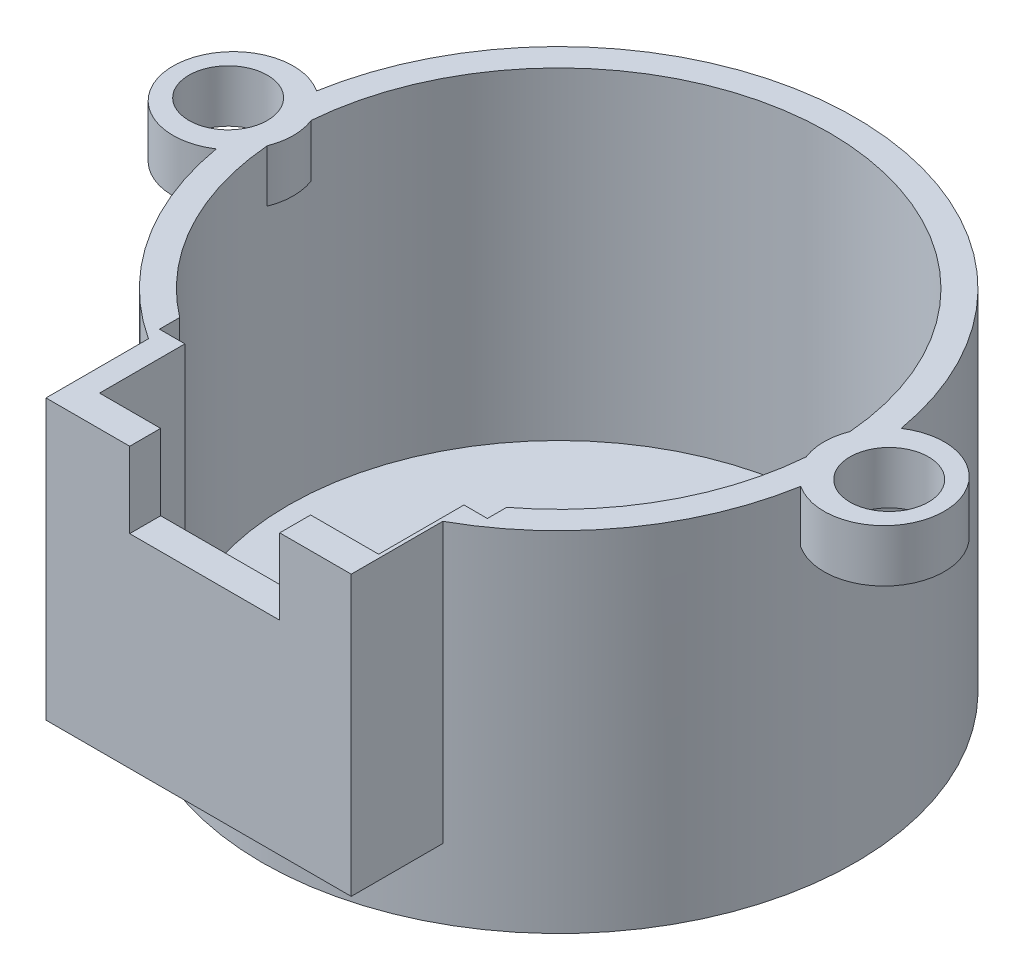
SolidWorks part; units mm, degrees
ref_plane "Front Plane" through (0, 0, 0) normal (0, 0, 1) x (1, 0, 0)
ref_plane "Top Plane" through (0, 0, 0) normal (0, 1, 0) x (1, 0, 0)
ref_plane "Right Plane" through (0, 0, 0) normal (1, 0, 0) x (0, 0, -1)
sketch "Sketch1" plane through (0, 0, 0) normal (0, 1, 0) x (1, 0, 0)
  circle A0 centre (0, 0) radius 17
  dimension "D1" = 34
extrude "Boss-Extrude1" add sketch "Sketch1" along normal blind 20
shell "Shell1" thickness 1.5
sketch "Sketch2" plane through (0, 20, 0) normal (0, 1, 0) x (1, 0, 0)
  line L0 (-15.5, 0) -> (37.717, 0) construction
  line L1 (0, 0) -> (0, -36.0151) construction
  circle A0 centre (0, 0) radius 15.5 construction
  circle A3 centre (18.6594, 0) radius 3.45
  circle A4 centre (-18.6594, 0) radius 3.45
extrude "Boss-Extrude3" add sketch "Sketch2" against normal blind 3
sketch "Sketch4" plane through (0, 20, 0) normal (0, 1, 0) x (1, 0, 0)
  line L0 (0, 0) -> (0, -29.7272) construction
  circle A0 centre (18.95, 0) radius 2.25
  circle A1 centre (-18.95, 0) radius 2.25
  dimension "D1" = 4.5
  dimension "D2" = 37.9
extrude "Cut-Extrude1" cut sketch "Sketch4" against normal blind 3
sketch "Sketch5" plane through (0, 20, 0) normal (0, 1, 0) x (1, 0, 0)
  line L1 (-9.2707, -12.4219) -> (8.2293, -12.4219)
  line L2 (-9.2707, -12.4219) -> (-9.2707, -20.1219)
  line L3 (-9.2707, -20.1219) -> (8.2293, -20.1219)
  line L4 (8.2293, -12.4219) -> (8.2293, -20.1219)
  circle A0 centre (0, 0) radius 15.5 construction
  dimension "D1" = 17.5
  dimension "D2" = 7.7
extrude "Boss-Extrude4" add sketch "Sketch5" against normal blind 16
sketch "Sketch6" plane through (0, 20, 0) normal (0, 1, 0) x (1, 0, 0)
  line L1 (-7.974, -18.3476) -> (8.026, -18.3476)
  line L2 (-7.974, -18.3476) -> (-7.974, -9.7476)
  line L3 (-7.974, -9.7476) -> (8.026, -9.7476)
  line L4 (8.026, -18.3476) -> (8.026, -9.7476)
  dimension "D1" = 16
  dimension "D2" = 8.6
extrude "Cut-Extrude2" cut sketch "Sketch6" against normal blind 14
sketch "Sketch7" plane through (0, 0, 20.1219) normal (0, 0, 1) x (1, 0, 0)
  line L1 (-4.4725, 15.661) -> (4.1275, 15.661)
  line L2 (-4.4725, 15.661) -> (-4.4725, 21.461)
  line L3 (-4.4725, 21.461) -> (4.1275, 21.461)
  line L4 (4.1275, 15.661) -> (4.1275, 21.461)
  dimension "D1" = 8.6
  dimension "D2" = 5.8
extrude "Cut-Extrude3" cut sketch "Sketch7" against normal blind 5
fillet "Fillet4" radius 1 1 edges at (-0.5207, 4, 12.4219)
sketch "Sketch8" plane through (0, 20, 0) normal (0, 1, 0) x (1, 0, 0)
  line L1 (-9.4317, -13.4558) -> (9.3683, -13.4558)
  line L2 (-9.4317, -13.4558) -> (-9.4317, -10.4558)
  line L3 (-9.4317, -10.4558) -> (9.3683, -10.4558)
  line L4 (9.3683, -13.4558) -> (9.3683, -10.4558)
  dimension "D1" = 18.8
  dimension "D2" = 3
extrude "Cut-Extrude4" cut sketch "Sketch8" against normal blind 16
